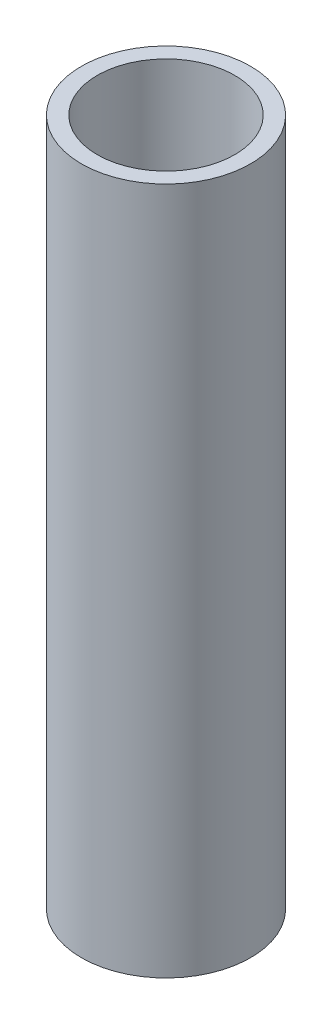
SolidWorks part; units mm, degrees
ref_plane "Front Plane" through (0, 0, 0) normal (0, 0, 1) x (1, 0, 0)
ref_plane "Top Plane" through (0, 0, 0) normal (0, 1, 0) x (1, 0, 0)
ref_plane "Right Plane" through (0, 0, 0) normal (1, 0, 0) x (0, 0, -1)
sketch "Sketch1" plane through (0, 0, 0) normal (0, 1, 0) x (1, 0, 0)
  circle A0 centre (0, 0) radius 3.075
  circle A1 centre (0, 0) radius 2.5
  dimension "D1" = 6.15
  dimension "D2" = 5
extrude "Boss-Extrude1" add sketch "Sketch1" along normal blind 25
